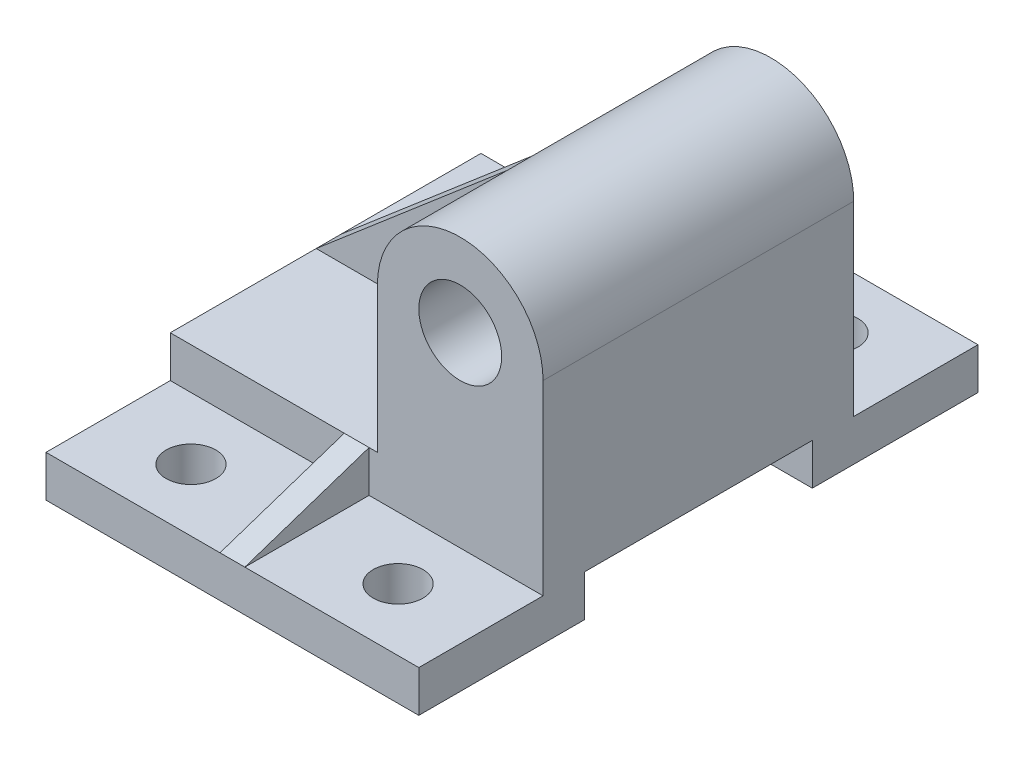
SolidWorks part; units mm, degrees
ref_plane "Front Plane" through (0, 0, 0) normal (0, 0, 1) x (1, 0, 0)
ref_plane "Top Plane" through (0, 0, 0) normal (0, 1, 0) x (1, 0, 0)
ref_plane "Right Plane" through (0, 0, 0) normal (1, 0, 0) x (0, 0, -1)
sketch "Sketch2" plane through (0, 0, 0) normal (0, 0, 1) x (1, 0, 0)
  line L0 (67.5, -37.5) -> (67.5, 17.5) construction
  line L2 (67.5, 17.5) -> (67.5, -37.5)
  line L3 (67.5, -37.5) -> (-22.5, -37.5)
  line L4 (-22.5, -17.5) -> (-22.5, -37.5)
  line L8 (27.5, 17.5) -> (27.5, -17.5)
  line L9 (27.5, -17.5) -> (-22.5, -17.5)
  arc A0 (67.5, 17.5) -> (27.5, 17.5) centre (47.5, 17.5) ccw
  circle A1 centre (47.5, 17.5) radius 10
  point P0 (0, 0)
  dimension "D6" = 20
  dimension "D1" = 90
  dimension "D3" = 55
  dimension "D7" = 20
extrude "Boss-Extrude1" add sketch "Sketch2" along normal blind 135
sketch "Sketch4" plane through (0, 0, 135) normal (0, 0, 1) x (1, 0, 0)
  line L1 (-17.3324, -24.6132) -> (-17.1225, -24.6132)
  line L2 (-22.5, -17.5) -> (-22.5, -27.5)
  line L3 (-22.5, -17.5) -> (-22.5, -37.5) construction
  line L4 (-22.5, -27.5) -> (67.5, -27.5)
  line L5 (67.5, -37.5) -> (67.5, 17.5) construction
  line L6 (67.5, -27.5) -> (67.5, -17.5)
  line L7 (67.5, -17.5) -> (-22.5, -17.5)
extrude "Cut-Extrude1" cut sketch "Sketch4" against normal blind 30
sketch "Sketch6" plane through (0, 0, 0) normal (0, 0, -1) x (-1, 0, 0)
  line L0 (-67.5, -37.5) -> (-67.5, 17.5) construction
  line L1 (22.5, -27.5) -> (-67.5, -27.5)
  line L2 (22.5, -27.5) -> (22.5, -17.5)
  line L3 (22.5, -17.5) -> (-67.5, -17.5)
  line L4 (-67.5, -27.5) -> (-67.5, -17.5)
  line L5 (22.5, -27.5) -> (-67.5, -17.5) construction
  line L6 (22.5, -17.5) -> (-67.5, -27.5) construction
  line L7 (-27.5, -17.5) -> (22.5, -17.5) construction
  point P0 (-22.5, -22.5)
  dimension "D1" = 90
  dimension "D2" = 10
  dimension "D3" = 0
  dimension "D4" = 0
extrude "Cut-Extrude2" cut sketch "Sketch6" against normal blind 30
sketch "Sketch9" plane through (0, 0, 0) normal (0, 0, -1) x (-1, 0, 0)
  line L0 (-67.5, -17.5) -> (-67.5, 17.5)
  line L3 (-67.5, -17.5) -> (-27.5, -17.5)
  line L4 (-27.5, -17.5) -> (-27.5, 17.5)
  arc A0 (-27.5, 17.5) -> (-67.5, 17.5) centre (-47.5, 17.5) ccw
  arc A1 (-27.5, 17.5) -> (-67.5, 17.5) centre (-47.5, 17.5) ccw construction
  dimension "D1" = 40
  dimension "D2" = 0
extrude "Cut-Extrude3" cut sketch "Sketch9" against normal blind 30
sketch "Sketch10" plane through (0, 0, 135) normal (0, 0, 1) x (1, 0, 0)
  line L0 (27.5, -17.5) -> (67.5, -17.5)
  line L1 (67.5, -17.5) -> (67.5, 17.5)
  line L2 (27.5, -17.5) -> (27.5, 17.5)
  arc A0 (67.5, 17.5) -> (27.5, 17.5) centre (47.5, 17.5) ccw
  arc A1 (67.5, 17.5) -> (27.5, 17.5) centre (47.5, 17.5) ccw construction
  dimension "D1" = 0
extrude "Cut-Extrude4" cut sketch "Sketch10" against normal blind 30
sketch "Sketch11" plane through (-22.5, 0, 0) normal (-1, 0, 0) x (0, 0, 1)
  line L0 (135, -37.5) -> (0, -37.5) construction
  line L1 (40, -47.5) -> (95, -47.5)
  line L2 (40, -47.5) -> (40, -27.5)
  line L3 (40, -27.5) -> (95, -27.5)
  line L4 (95, -47.5) -> (95, -27.5)
  line L5 (40, -47.5) -> (95, -27.5) construction
  line L6 (40, -27.5) -> (95, -47.5) construction
  point P0 (67.5, -37.5)
  dimension "D1" = 55
  dimension "D2" = 20
extrude "Cut-Extrude5" cut sketch "Sketch11" against normal through all
sketch "Sketch12" plane through (0, -27.5, 0) normal (0, 1, 0) x (1, 0, 0)
  line L0 (-22.5, -105) -> (-22.5, -135) construction
  line L1 (-22.5, -135) -> (67.5, -135) construction
  circle A0 centre (-2.5, -120) radius 6
  circle A1 centre (47.5, -120) radius 6
  point P6 (0, 0)
  point P8 (-1.8641, -121.0992)
  dimension "D2" = 12
  dimension "D3" = 12
  dimension "D1" = 20
  dimension "D4" = 50
  dimension "D5" = 0
  dimension "D6" = 15
extrude "Cut-Extrude6" cut sketch "Sketch12" against normal through all
sketch "Sketch13" plane through (0, -27.5, 0) normal (0, 1, 0) x (1, 0, 0)
  line L0 (67.5, -30) -> (67.5, 0) construction
  line L1 (-22.5, -30) -> (-22.5, 0) construction
  line L2 (67.5, 0) -> (-22.5, 0) construction
  circle A3 centre (47.5, -15) radius 6
  circle A4 centre (-2.5, -15) radius 6
  dimension "D1" = 12
  dimension "D2" = 12
  dimension "D3" = 20
  dimension "D4" = 20
  dimension "D5" = 15
  dimension "D6" = 15
extrude "Cut-Extrude7" cut sketch "Sketch13" against normal through all
sketch "Sketch14" plane through (0, -27.5, 0) normal (0, 1, 0) x (1, 0, 0)
  line L0 (-22.5, -135) -> (67.5, -135) construction
  line L1 (19.5, -105) -> (25.5, -105)
  line L2 (19.5, -105) -> (19.5, -135)
  line L3 (19.5, -135) -> (25.5, -135)
  line L4 (25.5, -105) -> (25.5, -135)
  line L5 (19.5, -105) -> (25.5, -135) construction
  line L6 (19.5, -135) -> (25.5, -105) construction
  line L7 (-22.5, -105) -> (-22.5, -135) construction
  point P0 (22.5, -120)
  dimension "D1" = 30
  dimension "D2" = 45
  dimension "D3" = 6
extrude "Boss-Extrude3" add sketch "Sketch14" along normal blind 10
sketch "Sketch15" plane through (0, -27.5, 0) normal (0, 1, 0) x (1, 0, 0)
  line L0 (67.5, -30) -> (-22.5, -30) construction
  line L1 (25.5, 0) -> (19.5, 0)
  line L2 (25.5, 0) -> (25.5, -30)
  line L3 (25.5, -30) -> (19.5, -30)
  line L4 (19.5, 0) -> (19.5, -30)
  line L5 (25.5, 0) -> (19.5, -30) construction
  line L6 (25.5, -30) -> (19.5, 0) construction
  line L7 (-22.5, -30) -> (-22.5, 0) construction
  point P0 (22.5, -15)
  dimension "D1" = 30
  dimension "D2" = 6
  dimension "D3" = 45
extrude "Boss-Extrude4" add sketch "Sketch15" along normal blind 10
sketch "Sketch16" plane through (19.5, 0, 0) normal (-1, 0, 0) x (0, 0, 1)
  line L0 (105, -17.5) -> (135, -27.5)
  line M3 (135, -27.5) -> (135, -17.5)
  line M4 (135, -17.5) -> (105, -17.5)
extrude "Cut-Extrude8" cut sketch "Sketch16" against normal through all and the other way through all contours L0 M4 M3
sketch "Sketch17" plane through (19.5, 0, 0) normal (-1, 0, 0) x (0, 0, 1)
  line L0 (30, -17.5) -> (0, -27.5)
  line M4 (30, -17.5) -> (0, -17.5)
  line M5 (0, -17.5) -> (0, -27.5)
extrude "Cut-Extrude9" cut sketch "Sketch17" against normal through all and the other way through all contours L0 M4 M5
sketch "Sketch18" plane through (27.5, 0, 0) normal (-1, 0, 0) x (0, 0, 1)
  line L0 (105, -17.5) -> (30, -17.5) construction
  line L1 (63.7772, 27.5) -> (69.7772, 27.5)
  line L2 (63.7772, 27.5) -> (63.7772, -17.5)
  line L3 (63.7772, -17.5) -> (69.7772, -17.5)
  line L4 (69.7772, 27.5) -> (69.7772, -17.5)
  line L5 (63.7772, 27.5) -> (69.7772, -17.5) construction
  line L6 (63.7772, -17.5) -> (69.7772, 27.5) construction
  point P0 (66.7772, 5)
  dimension "D1" = 6
  dimension "D2" = 45
extrude "Boss-Extrude5" add sketch "Sketch18" along normal blind 50 and the other way blind 10
sketch "Sketch19" plane through (0, 0, 63.7772) normal (0, 0, -1) x (-1, 0, 0)
  line L0 (22.5, -17.5) -> (-30.1795, 27.5)
  line M5 (22.5, -17.5) -> (22.5, 27.5)
  line M6 (22.5, 27.5) -> (-30.1795, 27.5)
extrude "Cut-Extrude10" cut sketch "Sketch19" against normal through all and the other way through all contours L0 M5 M6
